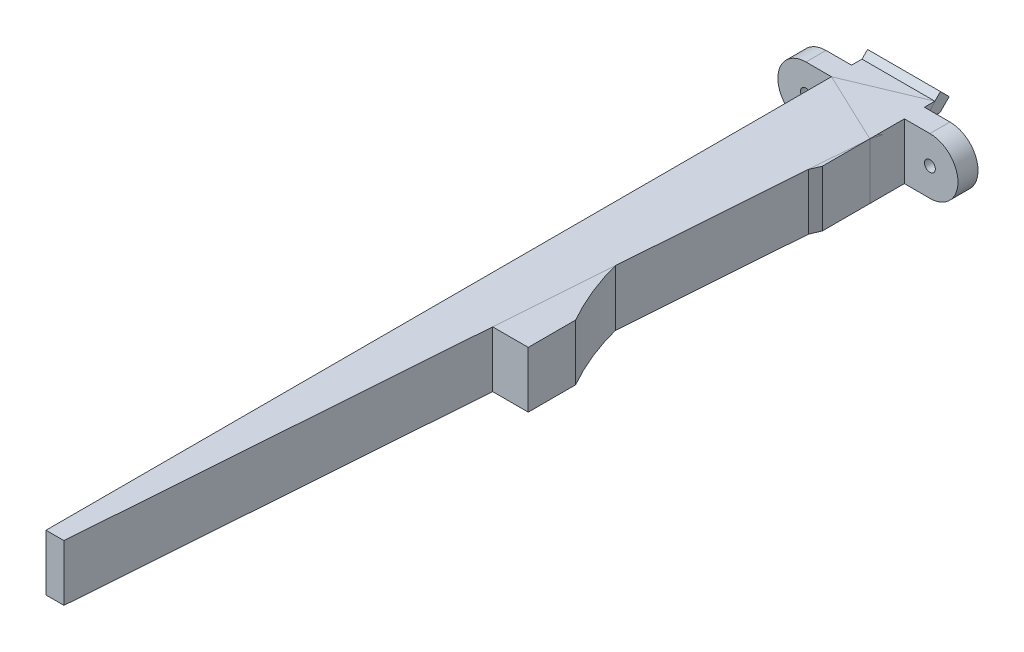
SolidWorks part; units mm, degrees
ref_plane "Front Plane" through (0, 0, 0) normal (0, 0, 1) x (1, 0, 0)
ref_plane "Top Plane" through (0, 0, 0) normal (0, 1, 0) x (1, 0, 0)
ref_plane "Right Plane" through (0, 0, 0) normal (1, 0, 0) x (0, 0, -1)
sketch "Sketch2" plane through (0, 0, 0) normal (0, 0, 1) x (1, 0, 0)
  line L0 (0, 5.9203) -> (0, 8.9503) construction
  line L1 (-5, -5.8182) -> (5, -5.8182)
  line L2 (-5, -5.8182) -> (-5, 8.9503)
  line L3 (-5, 8.9503) -> (5, 8.9503)
  line L4 (5, -5.8182) -> (5, 8.9503)
  line L7 (13.4766, 5.9203) -> (-18.5234, 5.9203) construction
  line L8 (0, -5.8182) -> (0, -2.7882) construction
  point P0 (0, 0)
  dimension "D1" = 10
extrude "Boss-Extrude1" add sketch "Sketch2" along normal blind 5
sketch "Sketch8" plane through (-5, 0, 0) normal (-1, 0, 0) x (0, 0, 1)
  line L6 (-0.15, 5.7703) -> (0, 5.7703)
  line L7 (0, 8.9503) -> (0, -5.8182) construction
  line L8 (0, 5.7703) -> (0, 4.0703)
  line L9 (0, 4.0703) -> (-0.15, 4.0703)
  line L11 (-0.15, -1.9297) -> (0, -1.9297)
  line L12 (-2.1379, 4.0703) -> (-0.15, 4.0703)
  line L13 (-0.15, 4.0703) -> (-0.15, 5.7703)
  line L14 (-0.15, 5.7703) -> (-1.4337, 5.7703)
  line L15 (-1.4337, 5.7703) -> (-2.2, 6.5366)
  line L16 (-2.2, 6.5366) -> (-3.4021, 5.3345)
  line L17 (-3.4021, 5.3345) -> (-2.1379, 4.0703)
  line L18 (-2.1379, 4.0703) -> (-0.15, 4.0703)
  line L20 (-0.15, 5.7703) -> (-1.4337, 5.7703)
  line L21 (-1.4337, 5.7703) -> (-2.2, 6.5366)
  line L22 (-2.2, 6.5366) -> (-3.4021, 5.3345)
  line L23 (-3.4021, 5.3345) -> (-2.1379, 4.0703)
  line L24 (-2.1379, -1.9297) -> (-0.15, -1.9297)
  line L25 (-0.15, -1.9297) -> (-0.15, -0.2297)
  line L26 (-0.15, -0.2297) -> (-1.4337, -0.2297)
  line L27 (-1.4337, -0.2297) -> (-2.2, 0.5366)
  line L28 (-2.2, 0.5366) -> (-3.4021, -0.6655)
  line L29 (-3.4021, -0.6655) -> (-2.1379, -1.9297)
  line L30 (-2.1379, -1.9297) -> (-0.15, -1.9297)
  line L32 (-0.15, -0.2297) -> (-1.4337, -0.2297)
  line L33 (-1.4337, -0.2297) -> (-2.2, 0.5366)
  line L34 (-2.2, 0.5366) -> (-3.4021, -0.6655)
  line L35 (-3.4021, -0.6655) -> (-2.1379, -1.9297)
  line L37 (-0.15, -0.2297) -> (0, -0.2297)
  line L38 (0, -1.9297) -> (0, -0.2297)
  dimension "D1" = 0.15
  dimension "D2" = 0.15
extrude "Boss-Extrude4" add sketch "Sketch8" against normal up to surface (10 mm away) up to face at (5, 1.566, 2.5)
sketch "Sketch9" plane through (0, 0, 0) normal (0, 0, -1) x (-1, 0, 0)
  line L4 (-5, 8.9503) -> (-5, 5.7703)
  line L5 (-5, 5.7703) -> (5, 5.7703)
  line L6 (5, 5.7703) -> (5, 8.9503)
  line L7 (5, 8.9503) -> (-5, 8.9503)
  line L8 (-5, 8.9503) -> (-5, 5.7703)
  line L10 (5, 5.7703) -> (5, 8.9503)
  line L11 (5, 8.9503) -> (-5, 8.9503)
  line L16 (5, -1.9297) -> (-5, -1.9297)
  line L17 (-5, -1.9297) -> (-5, -5.8182)
  line L18 (-5, -5.8182) -> (5, -5.8182)
  line L19 (5, -5.8182) -> (5, -1.9297)
  line L21 (-5, -1.9297) -> (-5, -5.8182)
  line L22 (-5, -5.8182) -> (5, -5.8182)
  line L23 (5, -5.8182) -> (5, -1.9297)
  line L26 (-5, 5.7703) -> (5, 5.7703)
  line L27 (5, -1.9297) -> (-5, -1.9297)
  dimension "D1" = 0
  dimension "D2" = 0
extrude "Cut-Extrude3" cut sketch "Sketch9" against normal blind 5
sketch "Sketch10" plane through (0, 5.7703, 0) normal (0, 1, 0) x (1, 0, 0)
  line L0 (-5, -5) -> (-5, -10.5)
  line L1 (-5, -10.5) -> (1.3524, -55.7)
  line L2 (1.3524, -55.7) -> (6.3524, -55.7)
  line L3 (-5, -5) -> (5, -5)
  line L4 (-120.9789, 453.7107) -> (412.3545, 453.7107) construction
  line L5 (6.3524, -55.7) -> (6.3524, -49.2)
  line L6 (5, -5) -> (5, -14)
  arc A1 (5, -14) -> (6.3524, -49.2) centre (39.6089, -30.2962) ccw
  dimension "D1" = 172
  dimension "D2" = 45.2
  dimension "D3" = 5
  dimension "D4" = 6.5
  dimension "D5" = 5.5
  dimension "D6" = 9
extrude "Boss-Extrude5" add sketch "Sketch10" against normal up to surface (7.7 mm away) up to face at (0, -1.9297, 1.4311)
ref_plane "Plane1" through (0, 0, 2.75) normal (0, 0, 1) x (1, 0, 0)
sketch "Sketch12" plane through (0, 0, 0) normal (0, 0, 1) x (1, 0, 0)
  line L0 (5, 5.7703) -> (8.5, 5.7703)
  line L1 (8.5, -1.9297) -> (5, -1.9297)
  line L2 (5, -1.9297) -> (5, 5.7703)
  line L3 (1.3524, 5.7703) -> (6.3524, 5.7703) construction
  line L4 (1.3524, -1.9297) -> (6.3524, -1.9297) construction
  line L5 (5, 5.3345) -> (5, 6.5366) construction
  line L6 (6.3524, 5.7703) -> (1.3552, 5.7703) construction
  arc A0 (8.5, 5.7703) -> (8.5, -1.9297) centre (8.5, 1.9203) cw
  circle A1 centre (8.5, 1.9203) radius 0.75
  dimension "D1" = 1.5
  dimension "D2" = 3.5
extrude "Boss-Extrude7" add sketch "Sketch12" along normal up to surface (2.75 mm away) up to plane "Plane1"
mirror "Mirror1" about plane through (0, 0, 0) normal (1, 0, 0) of bodies 112
fillet "Fillet1" radius 2.5 4 edges at (-6.3524, 1.9203, 49.2) (-5, 1.9203, 14) (-1.3524, 1.9203, 55.7) (-6.3524, 1.9203, 55.7)
sketch "Sketch13" plane through (0, 5.7703, 0) normal (0, 1, 0) x (1, 0, 0)
  line L1 (5, -10.5) -> (-8.6739, -10.5)
  line L2 (5, -10.5) -> (5, -58.128)
  line L3 (5, -58.128) -> (-8.6739, -58.128)
  line L4 (-8.6739, -10.5) -> (-8.6739, -58.128)
extrude "Cut-Extrude4" cut sketch "Sketch13" against normal blind 100
sketch "Sketch14" plane through (0, 0, 10.5) normal (0, 0, 1) x (1, 0, 0)
  line L1 (-5, 5.7703) -> (5, 5.7703)
  line L2 (-5, 5.7703) -> (-5, -1.9297)
  line L3 (-5, -1.9297) -> (5, -1.9297)
  line L4 (5, 5.7703) -> (5, -1.9297)
extrude "Boss-Extrude8" add sketch "Sketch14" along normal blind 100
sketch "Sketch15" plane through (0, 5.7703, 0) normal (0, 1, 0) x (1, 0, 0)
  line L0 (5, -7.4894) -> (-2.5387, -110.5)
  line L1 (5, -110.5) -> (5, 1.4337) construction
  line L2 (5, -110.5) -> (-5, -110.5) construction
  line L3 (-2.5387, -110.5) -> (5, -110.5)
  line L4 (5, -110.5) -> (5, -7.4894)
extrude "Cut-Extrude5" cut sketch "Sketch15" against normal blind 100
